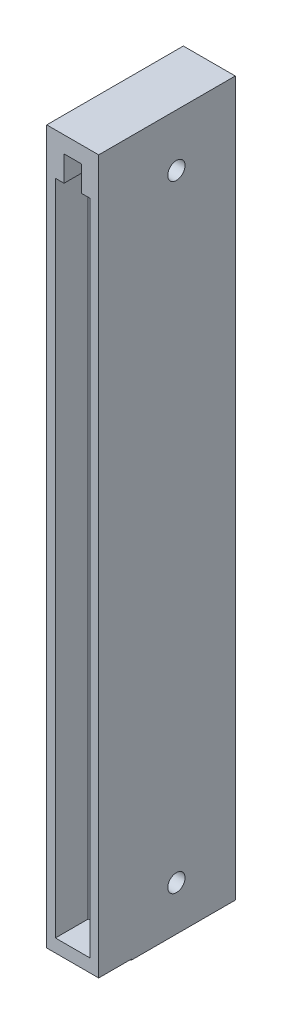
SolidWorks part; units mm, degrees
ref_plane "Front Plane" through (0, 0, 0) normal (0, 0, 1) x (1, 0, 0)
ref_plane "Top Plane" through (0, 0, 0) normal (0, 1, 0) x (1, 0, 0)
ref_plane "Right Plane" through (0, 0, 0) normal (1, 0, 0) x (0, 0, -1)
sketch "Sketch1" plane through (0, 0, 0) normal (0, 0, 1) x (1, 0, 0)
  line L1 (-4.6553, 6.2015) -> (-1.1553, 6.2015)
  line L2 (-4.6553, 6.2015) -> (-4.6553, -4.9782)
  line L3 (-4.6553, -4.9782) -> (-1.1553, -4.9782)
  line L4 (-1.1553, 6.2015) -> (-1.1553, -4.9782)
  dimension "D1" = 3.5
extrude "Boss-Extrude1" add sketch "Sketch1" along normal blind 6.89
sketch "Sketch3" plane through (-1.1553, 0, 0) normal (1, 0, 0) x (0, 0, -1)
  circle A0 centre (-2, 4.896) radius 0.5
extrude "Cut-Extrude1" cut sketch "Sketch3" against normal through all both and the other way through all
sketch "Sketch4" plane through (0, -4.9782, 0) normal (0, -1, 0) x (1, 0, 0)
  line L0 (-4.6553, 0) -> (-1.1553, 0) construction
  line L1 (-1.1553, 6.89) -> (-4.1553, 6.89)
  line L2 (-1.1553, 6.89) -> (-1.1553, 0)
  line L3 (-1.1553, 0) -> (-4.1553, 0)
  line L4 (-4.1553, 6.89) -> (-4.1553, 0)
  line L6 (-4.6553, 6.89) -> (-4.1553, 6.89)
  line L7 (-4.6553, 6.89) -> (-4.6553, 0)
  line L8 (-4.6553, 0) -> (-4.1553, 0)
  line L9 (-4.1553, 6.89) -> (-4.1553, 0)
  line M5 (-4.6553, 0) -> (-1.1553, 0)
  line M7 (-1.1553, 6.89) -> (-4.6553, 6.89)
  line M8 (-4.6553, 6.89) -> (-4.6553, 0)
  dimension "D1" = 3
extrude "Cut-Extrude2" cut sketch "Sketch4" against normal blind 15 contours L4 M7 M8 M5
sketch "Sketch5" plane through (0, -4.9782, 0) normal (0, -1, 0) x (1, 0, 0)
  line L1 (-4.1553, 6.89) -> (-1.1553, 6.89)
  line L2 (-4.1553, 6.89) -> (-4.1553, 0)
  line L3 (-4.1553, 0) -> (-1.1553, 0)
  line L4 (-1.1553, 6.89) -> (-1.1553, 0)
extrude "Boss-Extrude2" add sketch "Sketch5" along normal blind 13
sketch "Sketch6" plane through (0, -17.9782, 0) normal (0, -1, 0) x (1, 0, 0)
  line L1 (-4.1553, 6.89) -> (-1.1553, 6.89)
  line L2 (-4.1553, 6.89) -> (-4.1553, 0)
  line L3 (-4.1553, 0) -> (-1.1553, 0)
  line L4 (-1.1553, 6.89) -> (-1.1553, 0)
extrude "Boss-Extrude3" add sketch "Sketch6" along normal blind 17
sketch "Sketch7" plane through (0, 0, 0) normal (0, 0, -1) x (-1, 0, 0)
  line L0 (3.6542, 6.2015) -> (1.6565, 6.2015)
  line L1 (1.1553, 6.2015) -> (4.1553, 6.2015) construction
  line L3 (1.6565, 3.7806) -> (3.6542, 3.7806)
  line L4 (1.6565, 3.7806) -> (1.6565, -34.2252)
  line L5 (1.6565, -34.2252) -> (3.6542, -34.2252)
  line L6 (3.6542, 3.7806) -> (3.6542, -34.2252)
  point P5 (2.6553, 6.2015)
extrude "Cut-Extrude3" cut sketch "Sketch7" against normal through all contours L6 L3 L4 L5
sketch "Sketch8" plane through (-4.1553, 0, 0) normal (-1, 0, 0) x (0, 0, 1)
  line L0 (0, 6.2015) -> (-1, 6.2015)
  line L1 (6.89, 6.2015) -> (5, 6.2015)
  line L3 (-1, 6.2015) -> (5, 6.2015)
  line L4 (-1, 6.2015) -> (-1, -35.0299)
  line L5 (-1, -35.0299) -> (5, -35.0299)
  line L6 (5, 6.2015) -> (5, -35.0299)
extrude "Boss-Extrude4" add sketch "Sketch8" against normal up to surface (3 mm away) contours L4 L3 L6 L5 up to face at (-1.1553, 4.896, 2.5)
sketch "Sketch9" plane through (-4.1553, 0, 0) normal (-1, 0, 0) x (0, 0, 1)
  line L0 (-1, -35.0299) -> (-1, 6.2015) construction
  circle A0 centre (2.4, -32.4527) radius 0.5
  dimension "D1" = 3.4
extrude "Cut-Extrude4" cut sketch "Sketch9" against normal through all both and the other way through all
sketch "Sketch10" plane through (0, 0, -1) normal (0, 0, -1) x (-1, 0, 0)
  line L0 (1.1553, 6.2015) -> (2.1553, 6.2015)
  line L1 (1.1553, 6.2015) -> (4.1553, 6.2015) construction
  line L2 (2.1553, 6.2015) -> (3.1553, 6.2015)
  line L4 (2.1553, -31.192) -> (3.1553, -31.192)
  line L5 (2.1553, -31.192) -> (2.1553, 5.2509)
  line L6 (2.1553, 5.2509) -> (3.1553, 5.2509)
  line L7 (3.1553, -31.192) -> (3.1553, 5.2509)
extrude "Cut-Extrude5" cut sketch "Sketch10" against normal blind 42 contours L4 L7 L6 L5
sketch "Sketch11" plane through (-4.1553, 0, 0) normal (-1, 0, 0) x (0, 0, 1)
  line L0 (-1, -35.0299) -> (-1, 6.2015) construction
  circle A0 centre (2.4, 3.1769) radius 0.5
  dimension "D1" = 3.4
extrude "Cut-Extrude6" cut sketch "Sketch11" against normal through all both and the other way through all
